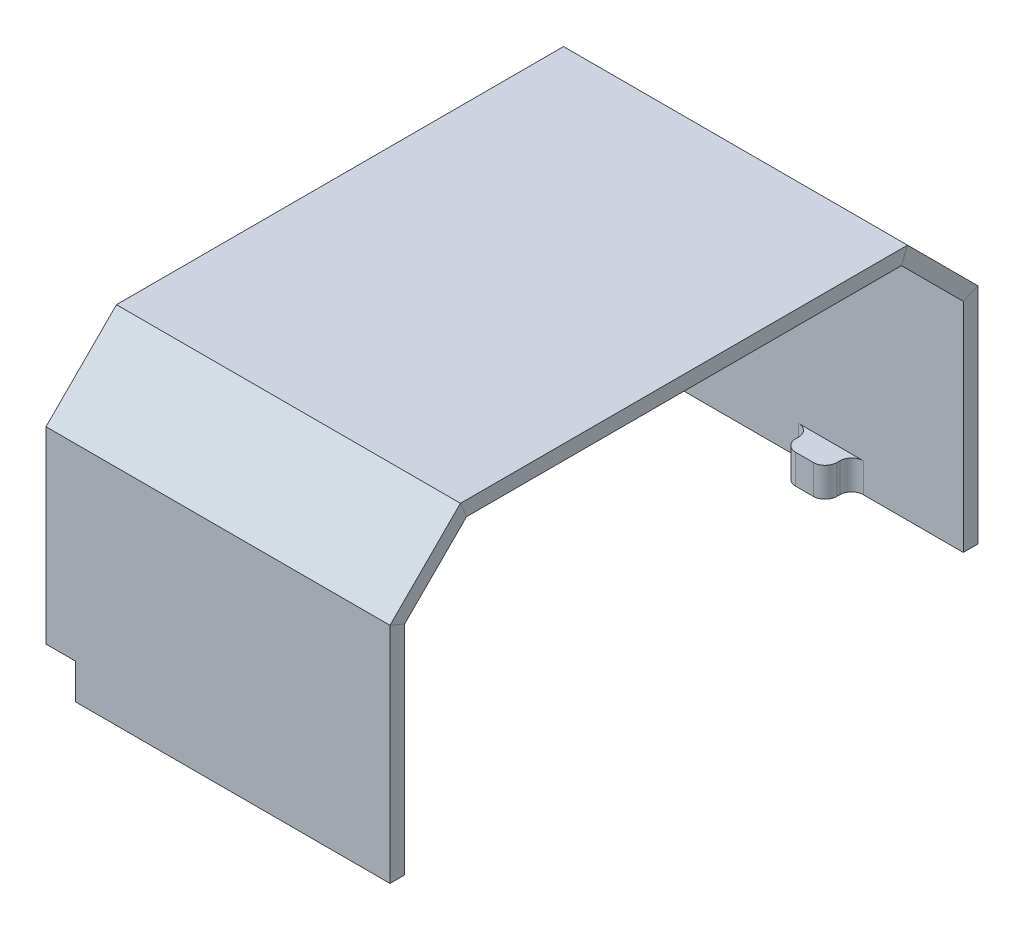
SolidWorks part; units mm, degrees
ref_plane "Front Plane" through (0, 0, 0) normal (0, 0, 1) x (1, 0, 0)
ref_plane "Top Plane" through (0, 0, 0) normal (0, 1, 0) x (1, 0, 0)
ref_plane "Right Plane" through (0, 0, 0) normal (1, 0, 0) x (0, 0, -1)
sketch "Sketch1" plane through (0, 0, 0) normal (0, 1, 0) x (1, 0, 0)
  line L1 (-50, -95) -> (50, -95)
  line L2 (-50, -95) -> (-50, -100)
  line L3 (-50, -100) -> (50, -100)
  line L4 (50, -95) -> (50, -100)
  line L5 (-50, -95) -> (50, -100) construction
  line L6 (-50, -100) -> (50, -95) construction
  line L7 (-50, 100) -> (50, 100) construction
  line L8 (-50, 100) -> (-50, 95) construction
  line L9 (-50, 95) -> (50, 95) construction
  line L10 (50, 100) -> (50, 95) construction
  line L11 (-50, 100) -> (50, 95) construction
  line L12 (-50, 95) -> (50, 100) construction
  point P4 (0, -97.5)
  point P9 (0, 97.5)
  dimension "D1" = 200
  dimension "D2" = 5
  dimension "D3" = 5
  dimension "D4" = 100
  dimension "D5" = 100
  dimension "D6" = 100
  dimension "D7" = 50
  dimension "D8" = 50
sketch "Sketch2" plane through (0, 0, 0) normal (1, 0, 0) x (0, 0, -1)
  line L0 (-97.5, 0) -> (-97.5, 75)
  line L1 (97.5, 0) -> (97.5, 75)
  line L2 (100, 0) -> (95, 0) construction
  line L3 (75, 97.5) -> (-75, 97.5)
  line L4 (-97.5, 75) -> (-75, 97.5)
  line L5 (75, 97.5) -> (97.5, 75)
  point P1 (0, 97.5)
  dimension "D1" = 150
  dimension "D2" = 0
  dimension "D3" = 97.5
  dimension "D4" = 0
sweep "Sweep3" add profiles "Sketch1" path "Sketch2"
ref_plane "Plane1" through (20, 0, 0) normal (1, 0, 0) x (0, 0, -1)
sketch "Sketch3" plane through (20, 0, 0) normal (1, 0, 0) x (0, 0, -1)
  line L1 (-100, 76.0355) -> (-76.0355, 100)
  line L2 (-76.0355, 100) -> (76.0355, 100)
  line L3 (76.0355, 100) -> (100, 76.0355)
  line L7 (95, 73.9645) -> (73.9645, 95)
  line L8 (73.9645, 95) -> (-73.9645, 95)
  line L9 (-73.9645, 95) -> (-95, 73.9645)
  line L12 (-100, 76.0355) -> (-95, 73.9645)
  line L13 (95, 73.9645) -> (100, 76.0355)
sketch "Sketch4" plane through (0, 100, 0) normal (0, 1, 0) x (1, 0, 0)
  point P0 (30.439, 28.6485)
sketch "Sketch5" plane through (-50, 0, 0) normal (-1, 0, 0) x (0, 0, 1)
  line L0 (-100, 0) -> (-95, 0)
  line L1 (-95, 0) -> (-95, 73.9645)
  line L2 (-95, 73.9645) -> (-73.9645, 95)
  line L3 (-73.9645, 95) -> (73.9645, 95)
  line L4 (73.9645, 95) -> (95, 73.9645)
  line L5 (95, 73.9645) -> (95, 0)
  line L6 (95, 0) -> (100, 0)
  line L7 (100, 0) -> (100, 76.0355)
  line L8 (100, 76.0355) -> (76.0355, 100)
  line L9 (76.0355, 100) -> (-76.0355, 100)
  line L10 (-76.0355, 100) -> (-100, 76.0355)
  line L11 (-100, 76.0355) -> (-100, 0)
extrude "Boss-Extrude1" add sketch "Sketch5" along normal blind 17
sketch "Sketch6" plane through (0, 0, -100) normal (0, 0, -1) x (-1, 0, 0)
  line L0 (57, 0) -> (57, 12)
  line L1 (67, 0) -> (-50, 0) construction
  line L2 (57, 12) -> (67, 12)
  line L3 (67, 76.0355) -> (67, 0) construction
  line L4 (67, 12) -> (67, 0)
  line L5 (67, 0) -> (57, 0)
  dimension "D1" = 10
  dimension "D2" = 12
extrude "Cut-Extrude1" cut sketch "Sketch6" against normal through all
sketch "Sketch7" plane through (0, 0, 0) normal (0, -1, 0) x (1, 0, 0)
  line L0 (50, 73.9645) -> (50, 95) construction
  line L6 (-2, 100) -> (12, 100)
  line L10 (-57, 100) -> (50, 100) construction
  line L11 (-2, 100) -> (-2, 86)
  line L12 (-2, 86) -> (12, 86)
  line L13 (12, 100) -> (12, 86)
  line L14 (-2, 100) -> (12, 86) construction
  line L15 (-2, 86) -> (12, 100) construction
  point P4 (-3.5, 86)
  point P5 (5, 93)
  dimension "D1" = 14
  dimension "D2" = 14
  dimension "D3" = 45
extrude "Boss-Extrude2" add sketch "Sketch7" against normal blind 10
sketch "Sketch8" plane through (0, 0, 0) normal (0, -1, 0) x (1, 0, 0)
  line L0 (-57, 100) -> (50, 100) construction
  line L1 (12, 86) -> (12, 95) construction
  circle A0 centre (5, 93) radius 6
  dimension "D1" = 12
  dimension "D2" = 7
  dimension "D3" = 7
extrude "Cut-Extrude2" cut sketch "Sketch8" against normal blind 2
fillet "Fillet1" radius 4 4 edges at (12, 5, 95) (-2, 5, 95) (-2, 5, 86) (12, 5, 86)
sketch "Sketch9" plane through (0, 0, 0) normal (0, -1, 0) x (1, 0, 0)
  line L0 (-57, -100) -> (50, -100) construction
  line L1 (-2, -100) -> (12, -100)
  line L2 (-2, -100) -> (-2, -86)
  line L3 (-2, -86) -> (12, -86)
  line L4 (12, -100) -> (12, -86)
  line L5 (-2, -100) -> (12, -86) construction
  line L6 (-2, -86) -> (12, -100) construction
  line L8 (50, -100) -> (50, -95) construction
  point P4 (5, -93)
  dimension "D1" = 14
  dimension "D2" = 14
  dimension "D3" = 45
extrude "Boss-Extrude3" add sketch "Sketch9" against normal blind 10
sketch "Sketch10" plane through (0, 0, 0) normal (0, -1, 0) x (1, 0, 0)
  line L0 (-57, -100) -> (50, -100) construction
  line L1 (-2, -86) -> (-2, -95) construction
  circle A0 centre (5, -93) radius 6
  dimension "D1" = 12
  dimension "D2" = 7
  dimension "D3" = 7
extrude "Cut-Extrude3" cut sketch "Sketch10" against normal blind 2
fillet "Fillet2" radius 4 4 edges at (12, 5, -86) (-2, 5, -95) (-2, 5, -86) (12, 5, -95)
